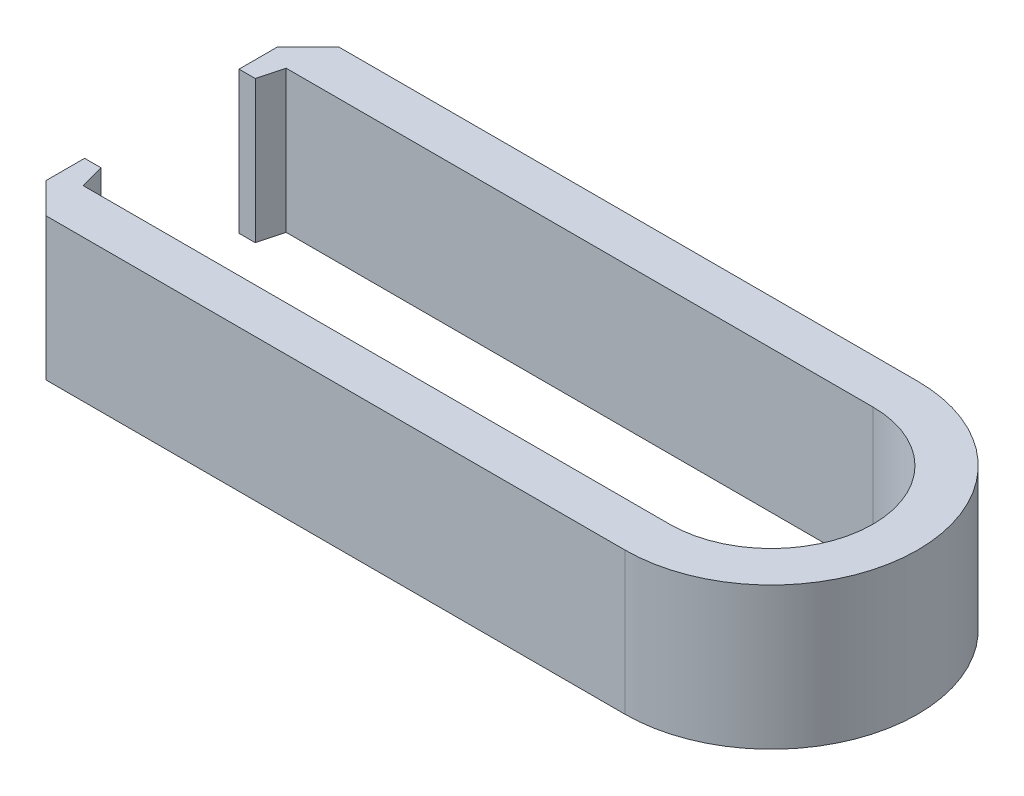
SolidWorks part; units mm, degrees
ref_plane "Front Plane" through (0, 0, 0) normal (0, 0, 1) x (1, 0, 0)
ref_plane "Top Plane" through (0, 0, 0) normal (0, 1, 0) x (1, 0, 0)
ref_plane "Right Plane" through (0, 0, 0) normal (1, 0, 0) x (0, 0, -1)
sketch "Sketch1" plane through (0, 0, 0) normal (0, 1, 0) x (1, 0, 0)
  line L0 (0, 5) -> (-30, 5)
  line L1 (-30, 5) -> (-30, 7.2)
  line L2 (-30, 7.2) -> (0, 7.2)
  line L3 (-30, 5) -> (-30, 3.8)
  line L4 (-30, 3.8) -> (-29.2, 3.8)
  line L5 (-29.2, 3.8) -> (-28.8785, 5)
  line L6 (-55, 0) -> (55, 0) construction
  line L7 (-29.2, -3.8) -> (-28.8785, -5)
  line L8 (-30, -3.8) -> (-29.2, -3.8)
  line L9 (-30, -5) -> (-30, -3.8)
  line L10 (-30, -5) -> (-30, -7.2)
  line L11 (0, -5) -> (-30, -5)
  line L12 (-30, -7.2) -> (0, -7.2)
  circle A0 centre (0, 0) radius 5
  circle A1 centre (0, 0) radius 7.2
  dimension "D1" = 10
  dimension "D3" = 30
  dimension "D4" = 1.2
  dimension "D5" = 0.8
  dimension "D6" = 105
  dimension "D2" = 2.2
extrude "Boss-Extrude1" add sketch "Sketch1" along normal blind 7 contours L11 L7 L8 L9 | A1 L11 L10 L12 | A1 L0 A0 L11 | L4 L5 L0 L3 | A1 L2 L1 L0
chamfer "Chamfer1" distance 1.5 angle 45 2 edges at (-30, 3.5, 7.2) (-30, 3.5, -7.2)
